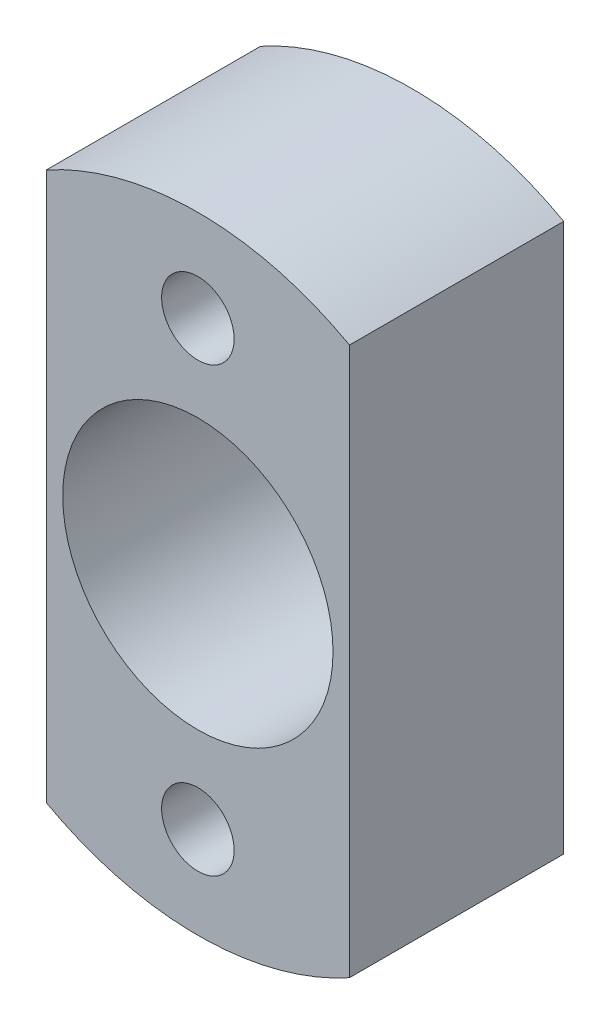
SolidWorks part; units mm, degrees
ref_plane "Front Plane" through (0, 0, 0) normal (0, 0, 1) x (1, 0, 0)
ref_plane "Top Plane" through (0, 0, 0) normal (0, 1, 0) x (1, 0, 0)
ref_plane "Right Plane" through (0, 0, 0) normal (1, 0, 0) x (0, 0, -1)
ref_plane "Plane1" through (0, 0, 9.5) normal (0, 0, 1) x (1, 0, 0)
sketch "Sketch1" plane through (0, 0, 0) normal (0, 0, 1) x (1, 0, 0)
  line L0 (0, 0) -> (0, 9.5) construction
  line L1 (-4.6, -8.312) -> (-4.6, 8.312)
  line L2 (4.6, -8.312) -> (4.6, 8.312)
  arc A0 (-4.6, -8.312) -> (4.6, -8.312) centre (0, 0) ccw
  arc A1 (4.6, 8.312) -> (-4.6, 8.312) centre (0, 0) ccw
  dimension "D1" = 19
  dimension "D2" = 9.2
extrude "Extrude1" add sketch "Sketch1" along normal blind 6.5
sketch "Sketch3" plane through (0, 0, 6.5) normal (0, 0, 1) x (1, 0, 0)
  line L0 (0, 0) -> (4.6, 0) construction
  line L1 (4.6, -8.312) -> (4.6, 8.312) construction
  circle A0 centre (0, 6.715) radius 1.1
  circle A1 centre (0, -6.715) radius 1.1
  dimension "D1" = 2.2
  dimension "D2" = 13.43
extrude "Cut-Extrude1" cut sketch "Sketch3" against normal through all
sketch "Sketch5" plane through (0, 0, 0) normal (0, 0, -1) x (-1, 0, 0)
  circle A0 centre (0, 0) radius 4.1
  dimension "D1" = 8.2
extrude "Cut-Extrude2" cut sketch "Sketch5" against normal blind 24
